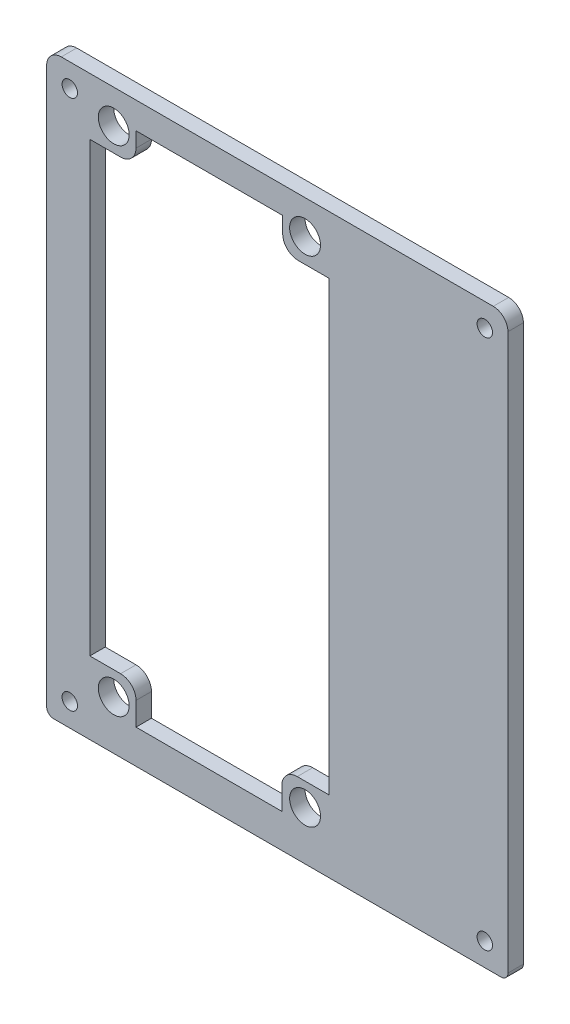
SolidWorks part; units mm, degrees
ref_plane "前视基准面" through (0, 0, 0) normal (0, 0, 1) x (1, 0, 0)
ref_plane "上视基准面" through (0, 0, 0) normal (0, 1, 0) x (1, 0, 0)
ref_plane "右视基准面" through (0, 0, 0) normal (1, 0, 0) x (0, 0, -1)
other "Configuration Table"
sketch "草图2" plane through (0, 0, 0) normal (0, 0, 1) x (1, 0, 0)
  line L21 (-56.4736, -0.8961) -> (1.5264, -0.8961)
  line L22 (2.4264, 72.0039) -> (2.4264, 0.0039)
  line L23 (-55.4736, 73.9039) -> (0.5264, 73.9039)
  line L24 (-57.3736, 72.0039) -> (-57.3736, 0.0039)
  circle A0 centre (-54.3736, 70.9039) radius 1
  circle A7 centre (-0.5736, 70.9039) radius 1
  circle A9 centre (-0.5736, 2.1039) radius 1
  circle A11 centre (-54.3736, 2.1039) radius 1
  arc A26 (1.5264, -0.8961) -> (2.4264, 0.0039) centre (1.5264, 0.0039) ccw
  arc A27 (2.4264, 72.0039) -> (0.5264, 73.9039) centre (0.5264, 72.0039) ccw
  arc A28 (-57.3736, 72.0039) -> (-55.4736, 73.9039) centre (-55.4736, 72.0039) cw
  arc A29 (-56.4736, -0.8961) -> (-57.3736, 0.0039) centre (-56.4736, 0.0039) cw
  point P66 (2.5264, -0.9961)
  point P69 (-57.4736, -0.9961)
  dimension "D4" = 3
  dimension "D1" = 2
  dimension "D3" = 3
  dimension "D6" = 3
  dimension "D11" = 2
  dimension "D21" = 2
  dimension "D23" = 2
  dimension "D5" = 3
  dimension "D7" = 3
  dimension "D8" = 3
  dimension "D9" = 3
  dimension "D10" = 3
  dimension "D19" = 60
extrude "凸台-拉伸1" add sketch "草图2" along normal blind 2
sketch "草图4" plane through (0, 0, 0) normal (0, 0, 1) x (1, 0, 0)
  line L0 (-51.7736, 8.5039) -> (-47.7864, 8.5039)
  line L1 (-45.7864, 6.5039) -> (-45.7864, 2.4039)
  line L3 (-51.7736, 70.4039) -> (-51.7736, 4.4039)
  line L5 (-20.7736, 70.5039) -> (-20.7736, 4.4007)
  line L6 (-20.7736, 8.4039) -> (-24.8864, 8.4039)
  line L7 (-26.8864, 6.4039) -> (-26.8864, 2.4039)
  line L8 (-51.7736, 66.5039) -> (-47.7864, 66.5039)
  line L9 (-45.7864, 68.5039) -> (-45.7864, 72.4039)
  line L10 (-26.7736, 72.5039) -> (-26.7736, 68.4039)
  line L11 (-24.7736, 66.4039) -> (-20.7736, 66.4039)
  line L12 (0.5264, 73.9039) -> (-55.4736, 73.9039) construction
  line L13 (-45.7864, 70.4539) -> (-26.7736, 70.4539)
  line L14 (-45.7864, 3.5039) -> (-26.8864, 3.5039)
  line L15 (-49.7736, 2.4039) -> (-45.7864, 2.4039)
  line L16 (-26.8864, 2.4039) -> (-22.8864, 2.4039)
  line L17 (-49.7736, 72.4039) -> (-45.7864, 72.4039)
  line L18 (-26.7736, 72.5039) -> (-22.7736, 72.5039)
  line L19 (-57.3736, 72.0039) -> (-57.3736, 0.0039) construction
  circle A0 centre (-48.6736, 69.5539) radius 2
  circle A1 centre (-23.8736, 69.5539) radius 2
  circle A2 centre (-23.8736, 5.4539) radius 2
  circle A3 centre (-48.6736, 5.4539) radius 2
  arc A4 (-49.7736, 2.4039) -> (-51.7736, 4.4039) centre (-49.7736, 4.4039) cw
  arc A5 (-22.8864, 2.4039) -> (-20.7736, 4.4007) centre (-22.7736, 4.4007) ccw
  arc A6 (-20.7736, 70.5039) -> (-22.7736, 72.5039) centre (-22.7736, 70.5039) ccw
  arc A7 (-51.7736, 70.4039) -> (-49.7736, 72.4039) centre (-49.7736, 70.4039) cw
  arc A8 (-47.7864, 66.5039) -> (-45.7864, 68.5039) centre (-47.7864, 68.5039) ccw
  arc A9 (-24.7736, 66.4039) -> (-26.7736, 68.4039) centre (-24.7736, 68.4039) cw
  arc A10 (-26.8864, 6.4039) -> (-24.8864, 8.4039) centre (-24.8864, 6.4039) cw
  arc A11 (-45.7864, 6.5039) -> (-47.7864, 8.5039) centre (-47.7864, 6.5039) ccw
  dimension "D3" = 3.1
  dimension "D15" = 2
  dimension "D16" = 2
  dimension "D9" = 4
  dimension "D2" = 31
  dimension "D4" = 70
  dimension "D7" = 1.5
  dimension "D8" = 5.6
  dimension "D5" = 2
  dimension "D6" = 2
extrude "切除-拉伸1" cut sketch "草图4" along normal blind 3
